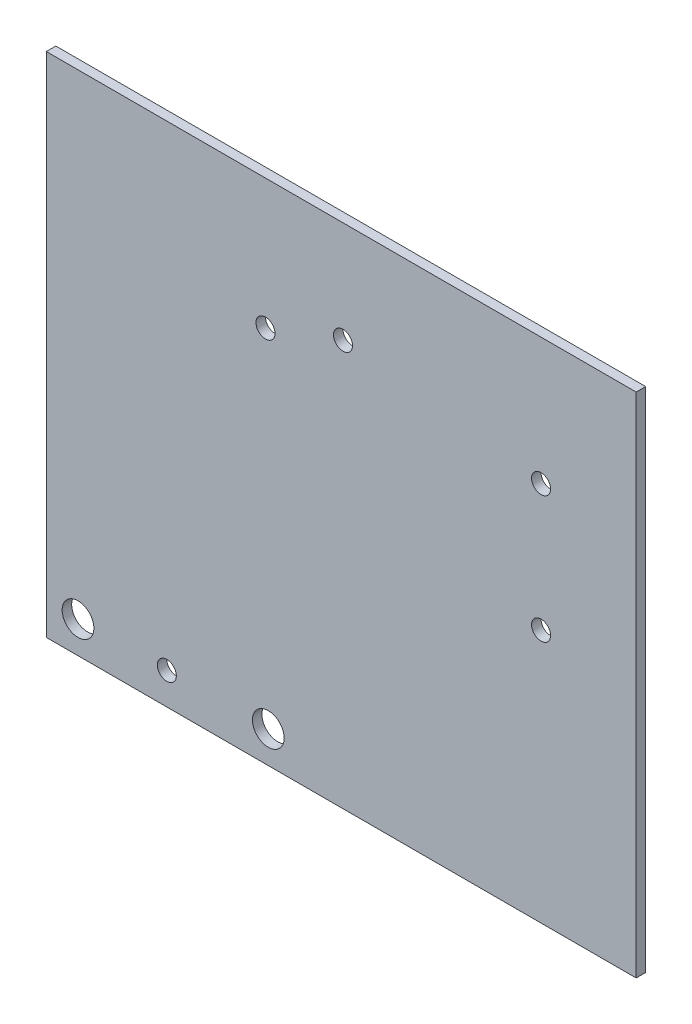
SolidWorks part; units mm, degrees
ref_plane "Front Plane" through (0, 0, 0) normal (0, 0, 1) x (1, 0, 0)
ref_plane "Top Plane" through (0, 0, 0) normal (0, 1, 0) x (1, 0, 0)
ref_plane "Right Plane" through (0, 0, 0) normal (1, 0, 0) x (0, 0, -1)
sketch "Sketch1" plane through (0, 0, 0) normal (0, 0, 1) x (1, 0, 0)
  line L1 (0, 0) -> (93, 0)
  line L2 (0, 0) -> (0, 80)
  line L3 (0, 80) -> (93, 80)
  line L4 (93, 0) -> (93, 80)
  dimension "D1" = 93
  dimension "D2" = 80
extrude "Boss-Extrude1" add sketch "Sketch1" along normal blind 1.5
hole_wizard "Ø5.0mm Press Dowel Hole1" positions "Sketch2" profile "Sketch3" hole size "Ø5.0" standard "AS"
sketch "Sketch2" plane through (19.8813, -7.7456, 0) normal (0, 0, -1) x (-1, 0, 0)
  point P0 (-15.1187, 12.7456)
  point P2 (14.8813, 12.7456)
sketch "Sketch3" plane through (35, 5, 0) normal (1, 0, 0) x (0, 1, 0)
  line L0 (0, 0) -> (0, 7.5022)
  line L1 (0, 7.5022) -> (2.5, 6)
  line L2 (2.5, 6) -> (2.5, 0)
  line L3 (2.5, 0) -> (0, 0)
  line L4 (0, 7.5022) -> (-2.5, 6) construction
  line L5 (0, -6.35) -> (0, 107.95) construction
  dimension "Hole Dia." = 5
  dimension "Hole Depth" = 6
  dimension "Drill Angle" = 118
hole_wizard "Ø3.0mm Dowel Hole1" positions "Sketch4" profile "Sketch5" hole size "Ø3.0" standard "ANSI Metric" end condition through all
sketch "Sketch4" plane through (19.8813, -7.7456, -1.5) normal (0, 0, -1) x (-1, 0, 0)
  point P0 (-26.893, 71.7107)
  point P2 (-14.677, 67.2644)
sketch "Sketch5" plane through (46.7743, 63.9651, -1.5) normal (1, 0, 0) x (0, 1, 0)
  line L0 (0, 0) -> (0, 3)
  line L1 (0, 3) -> (1.5, 3)
  line L2 (1.5, 3) -> (1.5, 0)
  line L3 (1.5, 0) -> (0, 0)
  line L4 (0, -6.35) -> (0, 107.95) construction
  dimension "Thru Hole Dia." = 3
  dimension "Thru Hole Depth" = 3
hole_wizard "Ø3.0mm Dowel Hole2" positions "Sketch6" profile "Sketch7" hole size "Ø3.0" standard "ANSI Metric"
sketch "Sketch6" plane through (19.8813, -7.7456, 0) normal (0, 0, -1) x (-1, 0, 0)
  point P0 (-58.1187, 67.7456)
  point P2 (-58.1187, 47.7456)
sketch "Sketch7" plane through (78, 60, 0) normal (1, 0, 0) x (0, 1, 0)
  line L0 (0, 0) -> (0, 3.9003)
  line L1 (0, 3.9003) -> (1.5, 2.999)
  line L2 (1.5, 2.999) -> (1.5, 0)
  line L3 (1.5, 0) -> (0, 0)
  line L4 (0, 3.9003) -> (-1.5, 2.999) construction
  line L5 (0, -6.35) -> (0, 107.95) construction
  dimension "Hole Dia." = 3
  dimension "Hole Depth" = 2.999
  dimension "Drill Angle" = 118
hole_wizard "Ø3.0mm Dowel Hole3" positions "Sketch8" profile "Sketch9" hole size "Ø3.0" standard "ANSI Metric" end condition through all
sketch "Sketch8" plane through (19.8813, -7.7456, 3) normal (0, 0, 1) x (1, 0, 0)
  point P0 (-0.8813, 12.7456)
sketch "Sketch9" plane through (19, 5, 3) normal (1, 0, 0) x (0, -1, 0)
  line L0 (0, 0) -> (0, 3)
  line L1 (0, 3) -> (1.5, 3)
  line L2 (1.5, 3) -> (1.5, 0)
  line L3 (1.5, 0) -> (0, 0)
  line L4 (0, -6.35) -> (0, 107.95) construction
  dimension "Thru Hole Dia." = 3
  dimension "Thru Hole Depth" = 3
